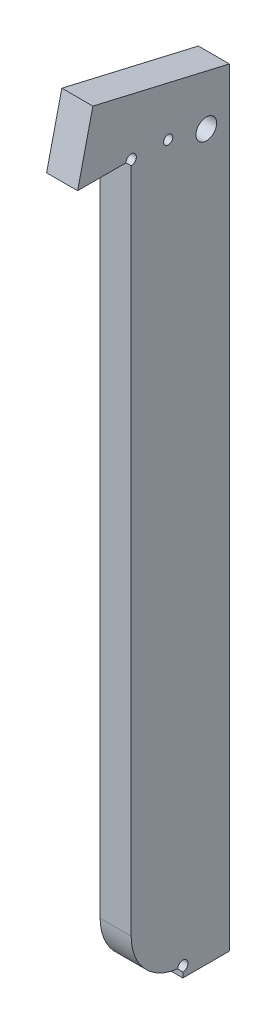
SolidWorks part; units mm, degrees
material "MDF"
ref_plane "Front Plane" through (0, 0, 0) normal (0, 0, 1) x (1, 0, 0)
ref_plane "Top Plane" through (0, 0, 0) normal (0, 1, 0) x (1, 0, 0)
ref_plane "Right Plane" through (0, 0, 0) normal (1, 0, 0) x (0, 0, -1)
sketch "Sketch1" plane through (0, 0, 0) normal (0, 0, 1) x (1, 0, 0)
  line L0 (-188.3336, -463.55) -> (-104.775, -463.55) construction
  line L1 (-228.0888, 0) -> (-209.0388, 0)
  line L2 (-228.0888, 0) -> (-228.0888, -450.85)
  line L3 (-228.0888, -450.85) -> (-209.0388, -450.85)
  line L4 (-209.0388, 0) -> (-209.0388, -450.85)
  dimension "D1" = 19.05
  dimension "D2" = 12.7
extrude "Boss-Extrude1" add sketch "Sketch1" along normal blind 66.675
fillet "Fillet4" radius 38.1 1 edges at (-218.5638, -450.85, 66.675)
sketch "Sketch4" plane through (-228.0888, 0, 0) normal (-1, 0, 0) x (0, 0, 1)
  line L1 (66.675, 0) -> (66.675, -412.75) construction
  line L3 (66.675, 0) -> (66.675, -412.75)
  line L4 (60.325, 0) -> (60.325, -412.75)
  line L5 (28.575, -450.85) -> (28.575, -444.5)
  line L6 (66.675, 0) -> (60.325, 0)
  arc A1 (28.575, -450.85) -> (66.675, -412.75) centre (28.575, -412.75) ccw construction
  arc A3 (28.575, -450.85) -> (66.675, -412.75) centre (28.575, -412.75) ccw
  arc A4 (28.575, -444.5) -> (60.325, -412.75) centre (28.575, -412.75) ccw
  dimension "D1" = 6.35
extrude "Cut-Extrude1" cut sketch "Sketch4" against normal up to next
sketch "Sketch7" plane through (-228.0888, 0, 0) normal (-1, 0, 0) x (0, 0, 1)
  line L0 (0, 0) -> (60.325, 0)
  line L1 (60.325, 0) -> (60.325, 34.8446)
  line L2 (495.3358, 135.9439) -> (380.7162, 109.3055) construction
  line L3 (60.325, 34.8446) -> (0, 20.8246)
  line L4 (0, 20.8246) -> (0, 0)
extrude "Boss-Extrude2" add sketch "Sketch7" against normal through all
sketch "Sketch8" plane through (-228.0888, 0, 0) normal (-1, 0, 0) x (0, 0, 1)
  line L0 (60.325, 34.8446) -> (83.8286, 40.3069)
  line L1 (83.8286, 40.3069) -> (93.1962, 0)
  line L2 (93.1962, 0) -> (60.325, 0)
  line L3 (60.325, 34.8446) -> (0, 20.8246) construction
  line L4 (60.325, 0) -> (60.325, 34.8446)
  dimension "D1" = 90
  dimension "D2" = 24.13
extrude "Boss-Extrude3" add sketch "Sketch8" against normal through all
chamfer "Chamfer1" [suppressed] distance 12.7 angle 45
hole_wizard "1/4 (0.25) Diameter Hole1" positions "Sketch5" profile "Sketch6" hole size "1/4" standard "ANSI Inch" end condition up to next
sketch "Sketch5" plane through (-228.0888, 0, 0) normal (-1, 0, 0) x (0, 0, 1)
  point P0 (28.575, -444.5)
  point P3 (60.325, 0)
sketch "Sketch6" plane through (-228.0888, -444.5, 28.575) normal (0, 1, 0) x (0, 0, 1)
  line L0 (0, 0) -> (0, 19.05)
  line L1 (0, 19.05) -> (3.175, 19.05)
  line L2 (3.175, 19.05) -> (3.175, 0)
  line L5 (3.175, 0) -> (0, 0)
  line L11 (0, -6.35) -> (0, 107.95) construction
  dimension "Thru Hole Dia." = 6.35
  dimension "Thru Hole Depth" = 19.05
hole_wizard "#10 Clearance Hole with 1.0 x .25 CB" positions "Sketch10" profile "Sketch11" legacy end condition up to next
sketch "Sketch10" plane through (-228.0888, 0, 0) normal (-1, 0, 0) x (0, 0, 1)
  point P0 (37.5801, -0.6606)
sketch "Sketch11" plane through (-228.0888, -0.6606, 37.5801) normal (0, 1, 0) x (0, 0, 1)
  line L0 (0, 0) -> (0, 19.05)
  line L1 (0, 19.05) -> (2.8067, 19.05)
  line L2 (2.8067, 19.05) -> (2.8067, 6.35)
  line L3 (2.8067, 6.35) -> (6.35, 6.35)
  line L4 (6.35, 6.35) -> (6.35, 0)
  line L5 (6.35, 0) -> (0, 0)
  line L6 (0, 110) -> (0, -10) construction
  dimension "Diameter" = 5.6134
  dimension "Depth" = 19.05
  dimension "C-Bore Diameter" = 12.7
  dimension "C-Bore Depth" = 6.35
hole_wizard "1/2 (0.5) Diameter Slot1" positions "Sketch14" profile "Sketch15" size "1/2" standard "ANSI Inch" slot yes end condition up to next
sketch "Sketch14" plane through (-228.0888, 0, 0) normal (-1, 0, 0) x (0, 0, 1)
  point P0 (14.1755, -6.6468)
  point P5 (0, 0)
  point P6 (0, 0)
sketch "Sketch15" plane through (-228.0888, -6.6468, 14.1755) normal (0, 1, 0) x (0, 0, 1)
  line L0 (0, 0) -> (0, 19.05)
  line L1 (0, 19.05) -> (6.35, 19.05)
  line L2 (6.35, 19.05) -> (6.35, 0)
  line L5 (6.35, 0) -> (0, 0)
  line L11 (0, -6.35) -> (0, 107.95) construction
  dimension "Thru Hole Dia." = 12.7
  dimension "Thru Hole Depth" = 19.05
